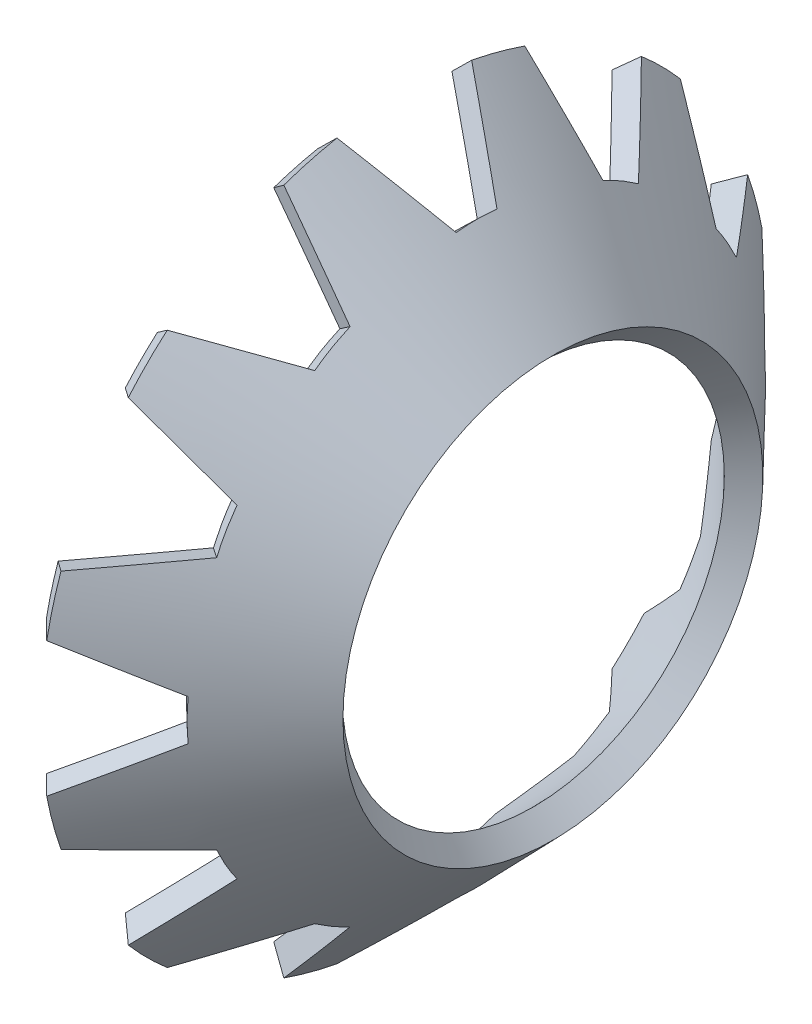
SolidWorks part; units mm, degrees
ref_plane "Plane1" through (0, 0, 0) normal (0, 0, 1) x (1, 0, 0)
ref_plane "Plane2" through (0, 0, 0) normal (0, 1, 0) x (1, 0, 0)
ref_plane "Plane3" through (0, 0, 0) normal (1, 0, 0) x (0, 0, -1)
sketch "SecSke" plane through (0, 0, 0) normal (0, 0, 1) x (1, 0, 0)
  line L0 (-34.925, 0) -> (9.525, 0) construction
  line L1 (-4.4584, 4.6168) -> (-7.7255, 8)
  line L3 (-8.1571, 7.5832) -> (-4.89, 4.2)
  line L4 (-4.89, 4.2) -> (-4.4584, 4.6168)
  line L5 (-8.1571, 7.5832) -> (-7.7255, 8)
  dimension "D1" = 46
  dimension "Outside_dia" = 16
  dimension "Inside_dia" = 8.4
  dimension "Thickness" = 0.6
  dimension "D2" = 4.7032
revolve "Base-Revolve" add sketch "SecSke" angle 360 about L0
ref_plane "CutPln" through (-7.7255, 8, 0) normal (0.7193, 0.6947, 0) x (0, 0, 1)
sketch "ExtCutSke" plane through (-7.7255, 8, 0) normal (0.7193, 0.6947, 0) x (0, 0, 1)
  line L1 (0, -13.1396) -> (0, 17.7379) construction
  line L2 (0, 0) -> (0, 8) construction
  line L3 (-0.4488, 2.2976) -> (-1.6388, -0.2386)
  line L4 (0.4488, 2.2976) -> (1.6388, -0.2386)
  arc A0 (-0.4488, 2.2976) -> (0.4488, 2.2976) centre (0, 8) ccw
  arc A1 (-1.6388, -0.2386) -> (1.6388, -0.2386) centre (0, 8) ccw
  ellipse E1 centre (0, 5.7547) end of major axis (-8, 5.7547) minor radius 5.7547 construction
  dimension "Clr_dia" = 16.8
  dimension "Cut_dia" = 11.44
  dimension "Cone_side" = 8
  dimension "Cut_ang" = 9
  dimension "Clr_ang" = 22.5
extrude "ExtCut" cut sketch "ExtCutSke" against normal through all
pattern_circular "ExtCuts" count 12 every 30 about axis through (-34.925, 0, 0) along (1, 0, 0) of "ExtCut"
equation "' \"Inside_dia@SecSke\" = 8.4"
equation "' \"Outside_dia@SecSke\" = 16"
equation "' \"Thickness@SecSke\" = 0.6"
equation "' \"Count@ExtCuts\" = 12"
equation "' \"Inside_dia@SecSke\" = 3.2"
equation "' \"Outside_dia@SecSke\" = 6"
equation "' \"Thickness@SecSke\" = 0.4"
equation "' \"Count@ExtCuts\" = 8"
equation " \"Cone_side@ExtCutSke\" = \"Outside_dia@SecSke\" / 2.0"
equation " \"Angle@ExtCuts\" = 360 / \"Count@ExtCuts\""
equation " \"Clr_dia@ExtCutSke\" =  \"Outside_dia@SecSke\" * 1.05"
equation " \"Cut_dia@ExtCutSke\" = \"Outside_dia@SecSke\" - (\"Outside_dia@SecSke\"  - \"Inside_dia@SecSke\" ) * 0.6"
equation " \"Clr_ang@ExtCutSke\" = (360 / \"Count@ExtCuts\") * 0.75"
equation " \"Cut_ang@ExtCutSke\" = (360 / \"Count@ExtCuts\") * 0.3"
